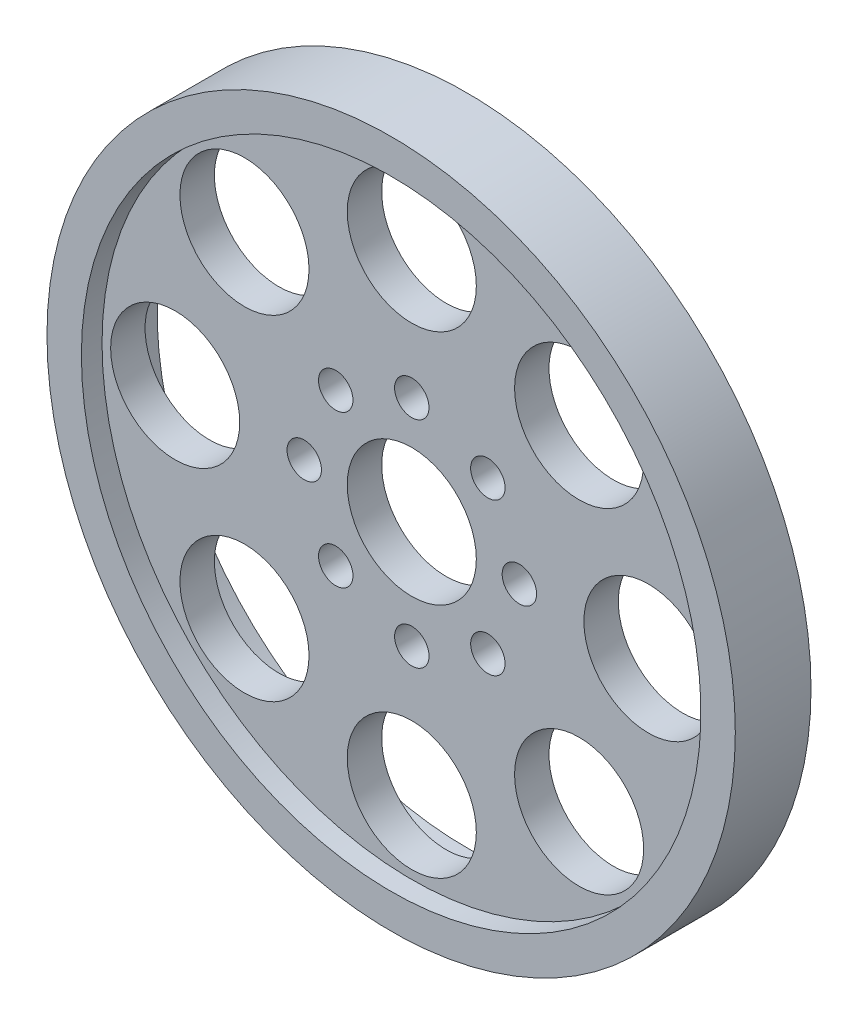
SolidWorks part; units mm, degrees
material "ABS"
ref_plane "Front Plane" through (0, 0, 0) normal (0, 0, 1) x (1, 0, 0)
ref_plane "Top Plane" through (0, 0, 0) normal (0, 1, 0) x (1, 0, 0)
ref_plane "Right Plane" through (0, 0, 0) normal (1, 0, 0) x (0, 0, -1)
sketch "Sketch1" plane through (0, 0, 0) normal (0, 0, 1) x (1, 0, 0)
  circle A0 centre (0, 0) radius 25.4
  dimension "D1" = 50.8
extrude "Boss-Extrude1" add sketch "Sketch1" along normal mid plane 5.588
sketch "Sketch2" plane through (0, 0, 2.794) normal (0, 0, 1) x (1, 0, 0)
  circle A0 centre (0, 0) radius 4.7625
  circle A1 centre (0, 0) radius 7.9375 construction
  circle A2 centre (0, 7.9375) radius 1.27
  circle A3 centre (5.613, 5.6134) radius 1.27
  circle A4 centre (7.9385, 0.001) radius 1.27
  circle A5 centre (5.6144, -5.612) radius 1.27
  circle A6 centre (0.002, -7.9375) radius 1.27
  circle A7 centre (-5.611, -5.6134) radius 1.27
  circle A8 centre (-7.9365, -0.001) radius 1.27
  circle A9 centre (-5.6124, 5.612) radius 1.27
  dimension "D1" = 9.525
  dimension "D2" = 15.875
  dimension "D3" = 2.54
  dimension "D4" = 8
extrude "Cut-Extrude1" cut sketch "Sketch2" against normal through all
sketch "Sketch3" plane through (0, 0, 0) normal (0, 0, 1) x (1, 0, 0)
  circle A0 centre (0, 0) radius 22.86
  dimension "D1" = 45.72
extrude "Cut-Extrude2" cut sketch "Sketch3" against normal blind 1.651 from offset 1.27
mirror "Mirror1" about plane through (0, 0, 0) normal (0, 0, 1) of "Cut-Extrude2"
sketch "Sketch4" plane through (0, 0, 0) normal (0, 0, 1) x (1, 0, 0)
  circle A0 centre (0, 0) radius 17.4625 construction
  circle A1 centre (0, 17.4625) radius 4.7625
  circle A2 centre (12.3479, 12.3479) radius 4.7625
  circle A3 centre (17.4625, 0) radius 4.7625
  circle A4 centre (12.3479, -12.3479) radius 4.7625
  circle A5 centre (0, -17.4625) radius 4.7625
  circle A6 centre (-12.3479, -12.3479) radius 4.7625
  circle A7 centre (-17.4625, 0) radius 4.7625
  circle A8 centre (-12.3479, 12.3479) radius 4.7625
  dimension "D1" = 34.925
  dimension "D2" = 9.525
  dimension "D3" = 8
extrude "Cut-Extrude3" cut sketch "Sketch4" against normal through all and the other way through all
